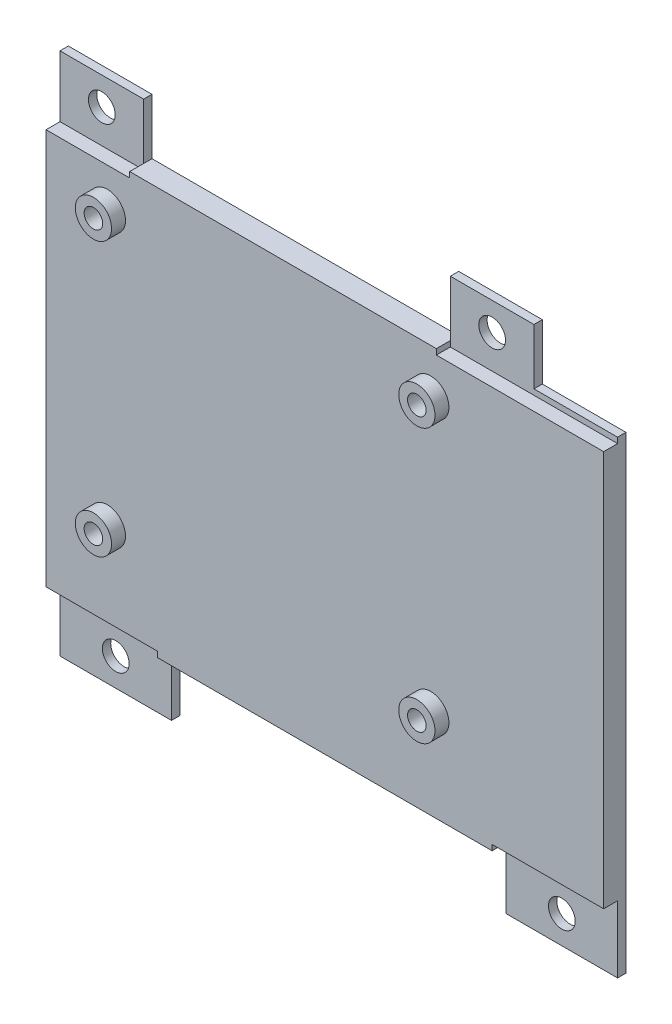
SolidWorks part; units mm, degrees
ref_plane "Front Plane" through (0, 0, 0) normal (0, 0, 1) x (1, 0, 0)
ref_plane "Top Plane" through (0, 0, 0) normal (0, 1, 0) x (1, 0, 0)
ref_plane "Right Plane" through (0, 0, 0) normal (1, 0, 0) x (0, 0, -1)
sketch "Sketch1" plane through (0, 0, 0) normal (0, 0, 1) x (1, 0, 0)
  line L1 (-50, 32.5) -> (50, 32.5)
  line L2 (-50, 32.5) -> (-50, -32.5)
  line L3 (-50, -32.5) -> (50, -32.5)
  line L4 (50, 32.5) -> (50, -32.5)
  line L5 (-50, 32.5) -> (50, -32.5) construction
  line L6 (-50, -32.5) -> (50, 32.5) construction
  point P0 (0, 0)
  dimension "D1" = 100
  dimension "D2" = 65
extrude "Boss-Extrude1" add sketch "Sketch1" along normal blind 1.5
sketch "Sketch2" plane through (0, 0, 1.5) normal (0, 0, 1) x (1, 0, 0)
  circle A0 centre (-39, 24.5) radius 1.665
  circle A1 centre (19, 24.5) radius 1.665
  circle A2 centre (19, -24.5) radius 1.665
  circle A3 centre (-39, -24.5) radius 1.665
  circle A4 centre (-39, 24.5) radius 3.25
  circle A5 centre (19, 24.5) radius 3.25
  circle A6 centre (19, -24.5) radius 3.25
  circle A7 centre (-39, -24.5) radius 3.25
  point P0 (-39, 24.5)
  point P1 (19, 24.5)
  point P3 (19, -24.5)
  point P5 (-39, -24.5)
  dimension "D1" = 3.33
  dimension "D2" = 6.5
extrude "Boss-Extrude2" add sketch "Sketch2" along normal blind 5
sketch "Sketch4" plane through (0, 0, 0) normal (0, 0, -1) x (-1, 0, 0)
  line L0 (-50, 32.5) -> (50, 32.5) construction
  line L1 (-50, -32.5) -> (-30, -32.5)
  line L2 (-50, -32.5) -> (-50, -51.5)
  line L3 (-50, -51.5) -> (-30, -51.5)
  line L4 (-30, -32.5) -> (-30, -51.5)
  line L5 (50, -32.5) -> (30, -32.5)
  line L6 (50, -32.5) -> (50, -51.5)
  line L7 (50, -51.5) -> (30, -51.5)
  line L8 (30, -32.5) -> (30, -51.5)
  line L9 (50, 32.5) -> (35, 32.5)
  line L10 (50, 32.5) -> (50, 42.5)
  line L11 (50, 42.5) -> (35, 42.5)
  line L12 (35, 32.5) -> (35, 42.5)
  line L13 (-35, 32.5) -> (-20, 32.5)
  line L14 (-35, 32.5) -> (-35, 42.5)
  line L15 (-35, 42.5) -> (-20, 42.5)
  line L16 (-20, 32.5) -> (-20, 42.5)
  line L17 (-35, 42.5) -> (-20, 32.5) construction
  line L18 (35, 42.5) -> (50, 32.5) construction
  line L19 (40, -32.5) -> (40, -51.5) construction
  line L20 (-40, -32.5) -> (-40, -51.5) construction
  line L21 (-50, -32.5) -> (-50, 32.5) construction
  line L22 (70.816, -41.635) -> (-58.516, -41.635) construction
  line L23 (70.816, -41.635) -> (-58.516, -41.635) construction
  line L24 (-30, -40.5) -> (30, -40.5)
  line L26 (50, -32.5) -> (-50, -32.5) construction
  line L28 (-64.5756, 21.6188) -> (-55.7145, 34.615)
  line L29 (-64.5756, 21.6188) -> (-55.7145, 34.615)
  line L30 (-55.7145, 34.615) -> (-37, 34.615)
  line L31 (-55.7145, 34.615) -> (-37, 34.615)
  line L32 (-37, 34.615) -> (-37, 41.615)
  line L58 (-37, 34.615) -> (-37, 41.615)
  line L59 (-37, 41.615) -> (-57.652, 41.615)
  line L60 (-37, 41.615) -> (-57.652, 41.615)
  line L61 (-60.4066, 40.1592) -> (-71.228, 24.2878)
  line L62 (-60.4066, 40.1592) -> (-71.228, 24.2878)
  line L63 (-72.85, 19.0296) -> (-72.85, -41.301)
  line L64 (-72.85, 19.0296) -> (-72.85, -41.301)
  line L65 (-63.516, -50.635) -> (-52, -50.635)
  line L66 (-63.516, -50.635) -> (-52, -50.635)
  line L67 (-52, -50.635) -> (-52, -43.635)
  line L69 (-52, -43.635) -> (-58.516, -43.635)
  line L70 (-52, -43.635) -> (-58.516, -43.635)
  line L71 (-65.85, -36.301) -> (-65.85, 17.4873)
  line L72 (-65.85, -36.301) -> (-65.85, 17.4873)
  line L83 (-52, -50.635) -> (-52, -43.635)
  circle A2 centre (42.5, 37.5) radius 2 construction
  circle A3 centre (-27.5, 37.5) radius 2 construction
  circle A4 centre (-40, -46.5) radius 2 construction
  circle A5 centre (40, -46.5) radius 2 construction
  arc A10 (-64.5756, 21.6188) -> (-65.85, 17.4873) centre (-58.516, 17.4873) ccw
  arc A11 (-64.5756, 21.6188) -> (-65.85, 17.4873) centre (-58.516, 17.4873) ccw
  arc A12 (-57.652, 41.615) -> (-60.4066, 40.1592) centre (-57.652, 38.281) ccw
  arc A13 (-57.652, 41.615) -> (-60.4066, 40.1592) centre (-57.652, 38.281) ccw
  arc A15 (-71.228, 24.2878) -> (-72.85, 19.0296) centre (-63.516, 19.0296) ccw
  arc A27 (-71.228, 24.2878) -> (-72.85, 19.0296) centre (-63.516, 19.0296) ccw
  arc A28 (-72.85, -41.301) -> (-63.516, -50.635) centre (-63.516, -41.301) ccw
  arc A29 (-72.85, -41.301) -> (-63.516, -50.635) centre (-63.516, -41.301) ccw
  arc A30 (-65.85, -36.301) -> (-58.516, -43.635) centre (-58.516, -36.301) ccw
  arc A31 (-65.85, -36.301) -> (-58.516, -43.635) centre (-58.516, -36.301) ccw
  dimension "D1" = 4
  dimension "D12" = 4
  dimension "D2" = 10
  dimension "D3" = 10
  dimension "D4" = 15
  dimension "D5" = 15
  dimension "D6" = 15
  dimension "D7" = 19
  dimension "D8" = 19
  dimension "D9" = 20
  dimension "D10" = 20
  dimension "D13" = 5
  dimension "D14" = 5
  dimension "D15" = 8
  dimension "D11" = 0
extrude "Boss-Extrude3" add sketch "Sketch4" against normal blind 1.5
sketch "Sketch7" plane through (0, 0, 0) normal (0, 0, -1) x (-1, 0, 0)
  point P0 (-40, -46.5)
  point P3 (40, -46.5)
  point P6 (42.5, 37.5)
  point P9 (-27.5, 37.5)
hole_wizard "M4 Clearance Hole1" positions "Sketch7" profile "Sketch6" hole size "M4" standard "ANSI Metric" end condition through all
sketch "Sketch6" plane through (40, -46.5, 0) normal (1, 0, 0) x (0, 1, 0)
  line L0 (0, 0) -> (0, 6.5)
  line L1 (0, 6.5) -> (2.4, 6.5)
  line L2 (2.4, 6.5) -> (2.4, 0)
  line L5 (2.4, 0) -> (0, 0)
  line L11 (0, -6.35) -> (0, 107.95) construction
  dimension "Thru Hole Dia." = 4.8
  dimension "Thru Hole Depth" = 6.5
sketch "Sketch8" plane through (0, 0, 1.5) normal (0, 0, 1) x (1, 0, 0)
  line L0 (50, -51.5) -> (50, 32.5) construction
  line L2 (-50, 32.5) -> (-50, -40.5)
  line L3 (-50, -40.5) -> (50, -40.5)
  line L4 (50, 32.5) -> (50, -40.5)
  line L5 (-50, 40.5) -> (50, -40.5) construction
  line L6 (-50, -40.5) -> (40.1235, 32.5) construction
  line L7 (30, -40.5) -> (-30, -40.5) construction
  line L8 (-50, 32.5) -> (50, 32.5)
  line L9 (-50, 31.5) -> (50, 31.5)
  line L10 (-50, -39.5) -> (50, -39.5)
  line L11 (-30, -40.5) -> (-30, -39.5)
  line L12 (30, -40.5) -> (30, -39.5)
  line L13 (20, 32.5) -> (20, 31.5)
  line L14 (35, 32.5) -> (35, 31.5)
  line L15 (-35, 32.5) -> (-35, 31.5)
  point P0 (0, 0)
  point P13 (0, 32.5)
  circle M10 centre (-39, -24.5) radius 3.25
  circle M11 centre (19, -24.5) radius 3.25
  circle M12 centre (19, 24.5) radius 3.25
  circle M13 centre (-39, 24.5) radius 3.25
  line M19 (20, 32.5) -> (-35, 32.5)
  line M25 (-30, -40.5) -> (30, -40.5)
  dimension "D1" = 1
  dimension "D2" = 1
extrude "Boss-Extrude4" add sketch "Sketch8" along normal blind 2.5 contours L2 L10 L4 L9 M11 M13 M12 M10 | L15 L9 L13 M19 | L12 L10 L11 M25
